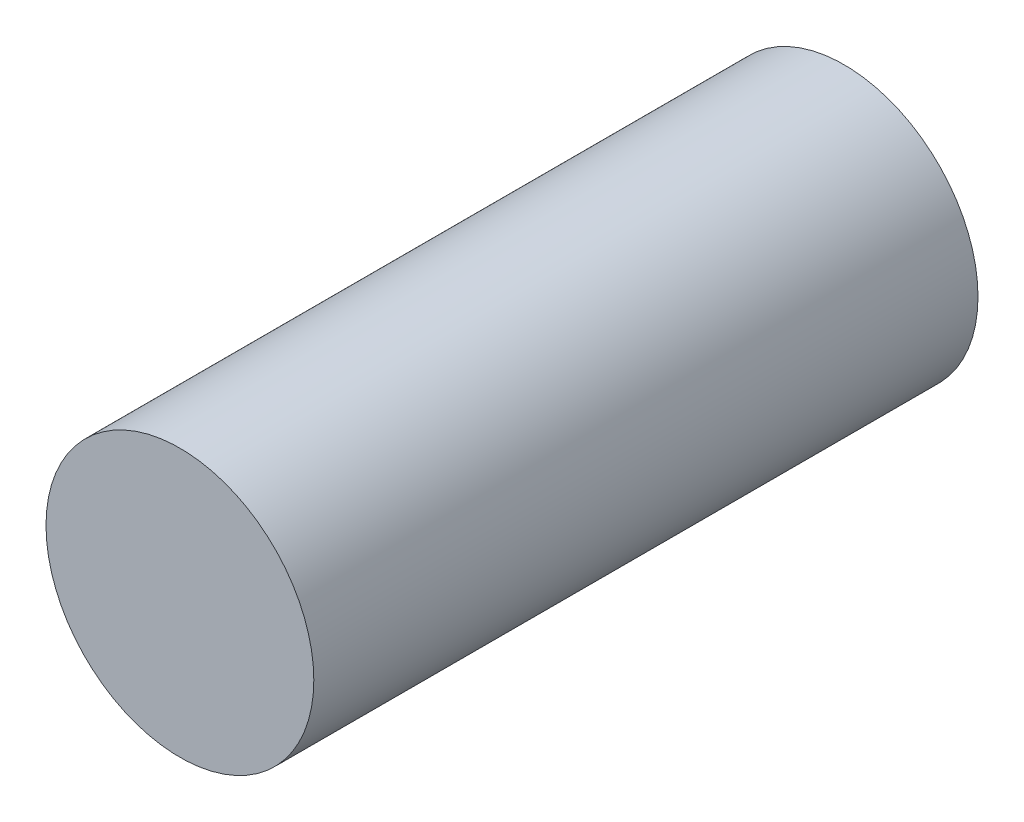
SolidWorks part; units mm, degrees
material "6061-T6 (SS)"
ref_plane "Front Plane" through (0, 0, 0) normal (0, 0, 1) x (1, 0, 0)
ref_plane "Top Plane" through (0, 0, 0) normal (0, 1, 0) x (1, 0, 0)
ref_plane "Right Plane" through (0, 0, 0) normal (1, 0, 0) x (0, 0, -1)
sketch "Body sketch" plane through (0, 0, 0) normal (0, 0, 1) x (1, 0, 0)
  circle A0 centre (0, 0) radius 2.5
extrude "Body" add sketch "Body sketch" along normal blind 12.4
